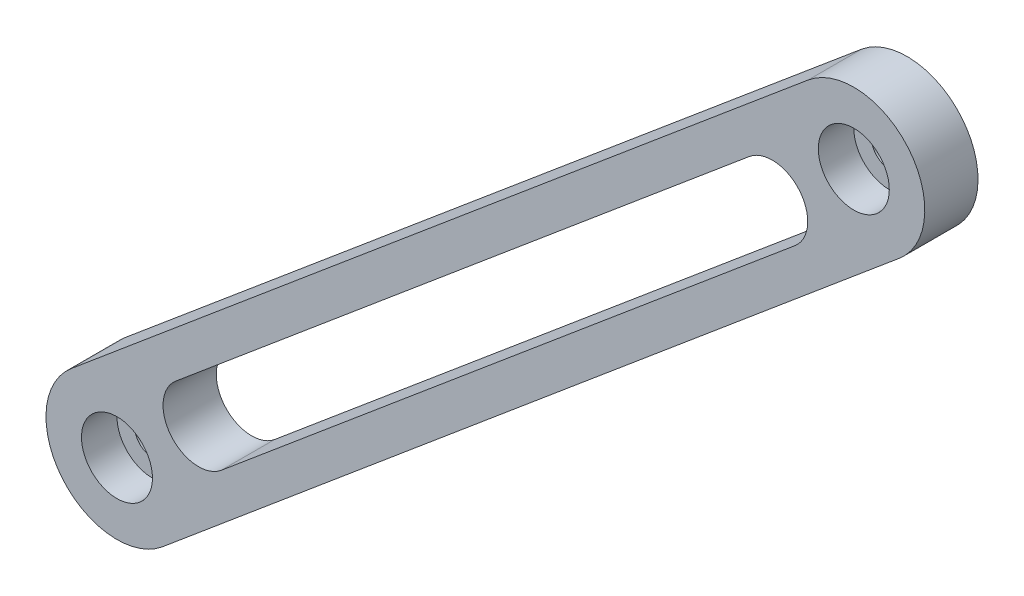
SolidWorks part; units mm, degrees
ref_plane "Front Plane" through (0, 0, 0) normal (0, 0, 1) x (1, 0, 0)
ref_plane "Top Plane" through (0, 0, 0) normal (0, 1, 0) x (1, 0, 0)
ref_plane "Right Plane" through (0, 0, 0) normal (1, 0, 0) x (0, 0, -1)
sketch "Sketch1" plane through (0, 0, 0) normal (0, 0, 1) x (1, 0, 0)
  line L0 (0, 0) -> (179.8502, 0) construction
  line L1 (8.1025, 0) -> (604.1295, 500.126) construction
  line L2 (604.1295, 500.126) -> (692.3152, 0) construction
  line L5 (568.3452, 503.2567) -> (304.6956, 282.0285)
  line L7 (600.9988, 464.3417) -> (337.3493, 243.1135)
  line L9 (555.4857, 459.309) -> (350.2087, 287.0612) construction
  line L10 (563.6491, 449.5802) -> (358.3721, 277.3324)
  line L11 (547.3223, 469.0378) -> (342.0453, 296.79)
  line L12 (321.0224, 262.571) -> (304.6956, 282.0285) construction
  line L13 (321.0224, 262.571) -> (337.3493, 243.1135) construction
  line L14 (568.3452, 503.2567) -> (600.9988, 464.3417) construction
  arc A0 (563.6491, 449.5802) -> (547.3223, 469.0378) centre (555.4857, 459.309) ccw
  arc A1 (342.0453, 296.79) -> (358.3721, 277.3324) centre (350.2087, 287.0612) ccw
  circle A2 centre (321.0224, 262.571) radius 6.35
  arc A3 (304.6956, 282.0285) -> (337.3493, 243.1135) centre (321.0225, 262.571) ccw
  circle A4 centre (584.672, 483.7992) radius 6.35
  arc A5 (568.3452, 503.2567) -> (600.9988, 464.3417) centre (584.672, 483.7992) cw
  point P12 (452.8472, 373.1851)
  point P24 (584.672, 483.7992)
  dimension "D6" = 12.7
  dimension "D7" = 12.7
  dimension "D4" = 25.4
  dimension "D3" = 25.4
  dimension "D1" = 40
  dimension "D2" = 80
  dimension "D5" = 267.97
  dimension "D8" = 38.1
  dimension "D9" = 38.1
extrude "Boss-Extrude1" add sketch "Sketch1" along normal blind 19.05
sketch "Sketch2" plane through (0, 0, 19.05) normal (0, 0, 1) x (1, 0, 0)
  circle A0 centre (321.0224, 262.571) radius 12.7
  circle A1 centre (584.672, 483.7992) radius 12.7
  dimension "D1" = 25.4
extrude "Cut-Extrude1" cut sketch "Sketch2" against normal blind 12.7
